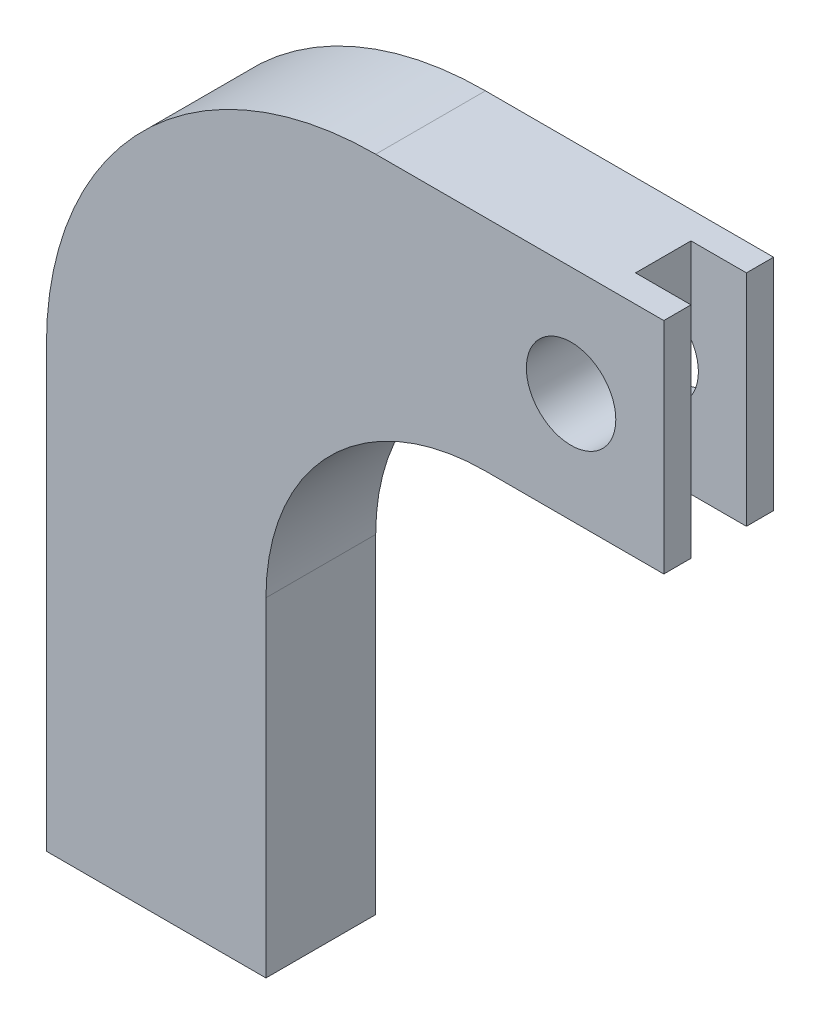
SolidWorks part; units mm, degrees
ref_plane "Front Plane" through (0, 0, 0) normal (0, 0, 1) x (1, 0, 0)
ref_plane "Top Plane" through (0, 0, 0) normal (0, 1, 0) x (1, 0, 0)
ref_plane "Right Plane" through (0, 0, 0) normal (1, 0, 0) x (0, 0, -1)
sketch "Sketch1" plane through (0, 0, 0) normal (0, 0, 1) x (1, 0, 0)
  line L0 (0, 0) -> (0, 8)
  line L1 (6, 14) -> (11.25, 14)
  line L2 (11.25, 14) -> (11.25, 10)
  line L3 (11.25, 10) -> (8, 10)
  line L4 (4, 6) -> (4, 0)
  line L5 (4, 0) -> (0, 0)
  arc A0 (0, 8) -> (6, 14) centre (6, 8) cw
  arc A1 (8, 10) -> (4, 6) centre (8, 6) ccw
  circle A2 centre (9.56, 12) radius 0.815
  point P9 (0, 14)
  dimension "D5" = 6
  dimension "D6" = 4
  dimension "D7" = 1.63
  dimension "D1" = 14
  dimension "D2" = 11.25
  dimension "D3" = 4
  dimension "D4" = 4
  dimension "D8" = 1.69
extrude "Boss-Extrude1" add sketch "Sketch1" along normal mid plane 2
sketch "Sketch2" plane through (11.25, 0, 0) normal (1, 0, 0) x (0, 0, -1)
  line L0 (0, 14) -> (0, 10) construction
  line L1 (-1, 14) -> (1, 14) construction
  line L2 (-1, 10) -> (1, 10) construction
  line L3 (-1, 10) -> (1, 10) construction
  line L4 (-0.505, 14) -> (0.505, 14)
  line L5 (-0.505, 14) -> (-0.505, 10)
  line L6 (-0.505, 10) -> (0.505, 10)
  line L7 (0.505, 14) -> (0.505, 10)
  dimension "D1" = 1.01
extrude "Cut-Extrude1" cut sketch "Sketch2" against normal blind 1.01
